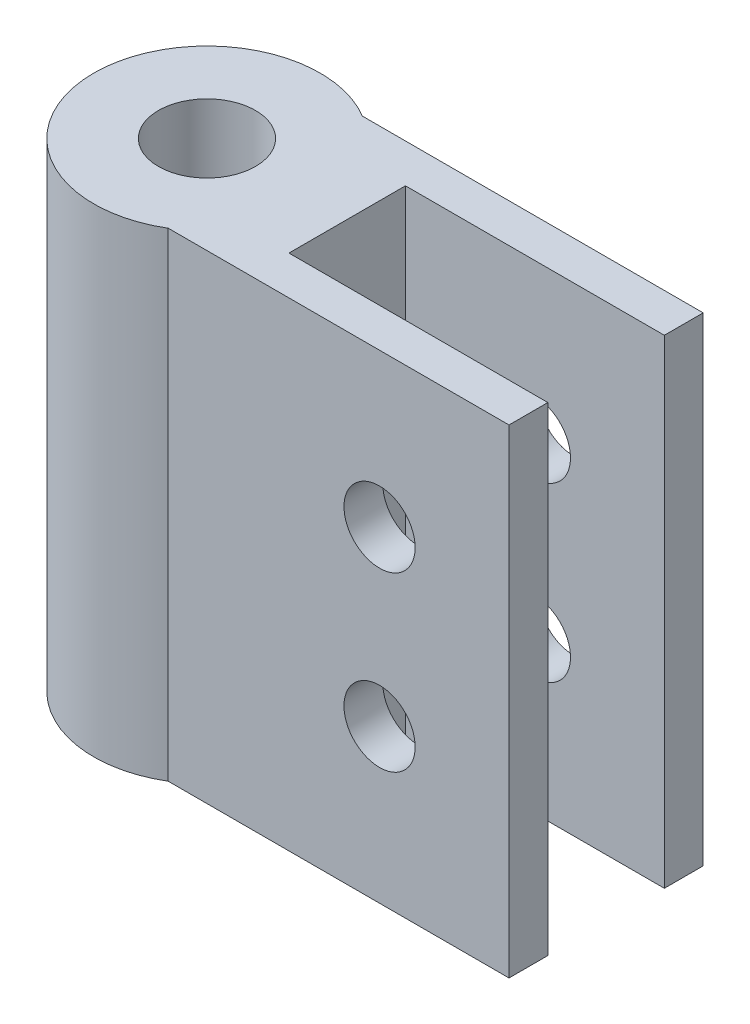
SolidWorks part; units mm, degrees
ref_plane "前视基准面" through (0, 0, 0) normal (0, 0, 1) x (1, 0, 0)
ref_plane "上视基准面" through (0, 0, 0) normal (0, 1, 0) x (1, 0, 0)
ref_plane "右视基准面" through (0, 0, 0) normal (1, 0, 0) x (0, 0, -1)
sketch "草图1" plane through (0, 0, 0) normal (0, 1, 0) x (1, 0, 0)
  circle A0 centre (0, 0) radius 2.25
  circle A1 centre (0, 0) radius 5.25
  dimension "D1" = 4.5
  dimension "D2" = 3
extrude "凸台-拉伸1" add sketch "草图1" along normal blind 22.2
sketch "草图2" plane through (0, 22.2, 0) normal (0, 1, 0) x (1, 0, 0)
  line L1 (18.5, -4.5) -> (2.5, -4.5)
  line L2 (18.5, -4.5) -> (18.5, 4.5)
  line L3 (18.5, 4.5) -> (2.5, 4.5)
  line L4 (2.5, -4.5) -> (2.5, 4.5)
  line L5 (18.5, -4.5) -> (2.5, 4.5) construction
  line L6 (18.5, 4.5) -> (2.5, -4.5) construction
  point P0 (10.5, 0)
  dimension "D1" = 10.5
  dimension "D2" = 16
  dimension "D3" = 9
extrude "凸台-拉伸2" add sketch "草图2" against normal up to surface (22.2 mm away) up to face at (0, 0, 5.25)
sketch "草图3" plane through (0, 22.2, 0) normal (0, 1, 0) x (1, 0, 0)
  line L0 (18.5, -4.5) -> (18.5, 4.5) construction
  line L1 (6.5, -2.7) -> (18.5, -2.7)
  line L2 (6.5, -2.7) -> (6.5, 2.7)
  line L3 (6.5, 2.7) -> (18.5, 2.7)
  line L4 (18.5, -2.7) -> (18.5, 2.7)
  line L5 (6.5, -2.7) -> (18.5, 2.7) construction
  line L6 (6.5, 2.7) -> (18.5, -2.7) construction
  point P0 (12.5, 0)
  dimension "D1" = 5.4
  dimension "D2" = 12
extrude "切除-拉伸1" cut sketch "草图3" against normal through all
sketch "草图4" plane through (0, 0, 4.5) normal (0, 0, 1) x (1, 0, 0)
  line L0 (6.5, 0) -> (6.5, 22.2) construction
  line L1 (6.5, 0) -> (6.5, 22.2) construction
  line L3 (18.5, 11.1) -> (2.7042, 11.1) construction
  line L4 (18.5, 0) -> (18.5, 22.2) construction
  line L5 (2.7042, 0) -> (2.7042, 22.2) construction
  circle A0 centre (12.5, 15.1) radius 1.65
  circle A2 centre (12.5, 7.1) radius 1.65
  dimension "D1" = 8
  dimension "D2" = 3.3
  dimension "D4" = 6
extrude "切除-拉伸2" cut sketch "草图4" against normal blind 22
